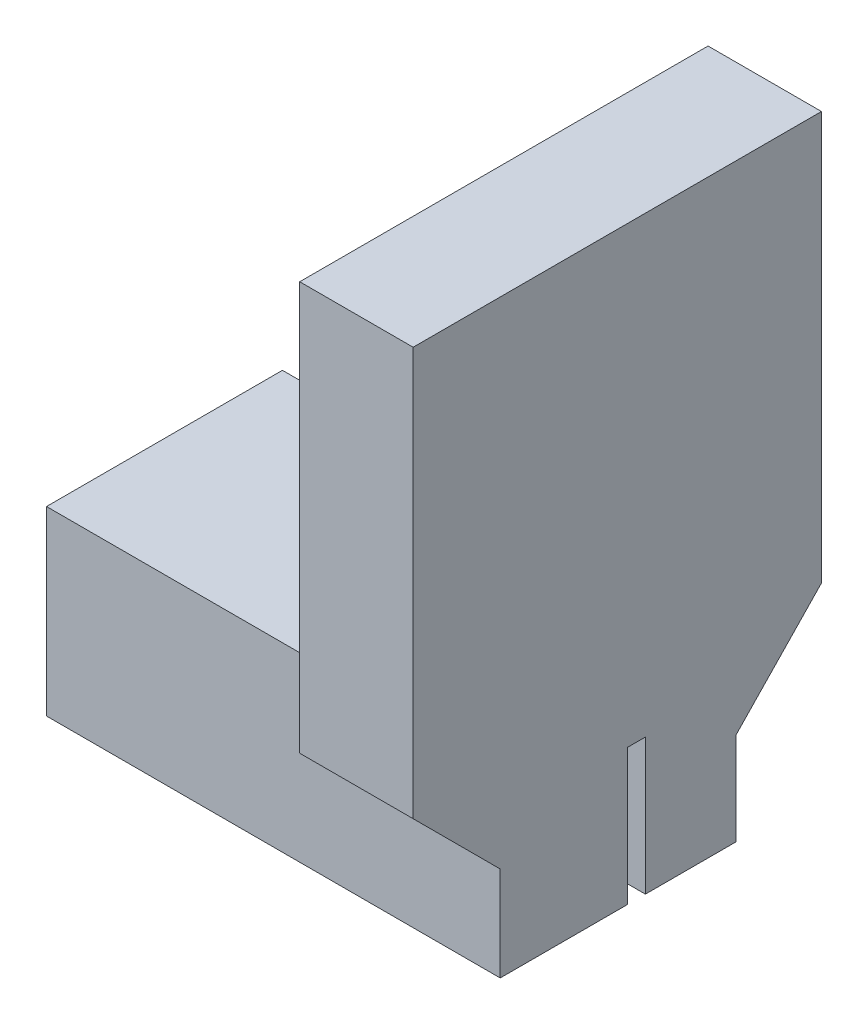
SolidWorks part; units mm, degrees
ref_plane "Front Plane" through (0, 0, 0) normal (0, 0, 1) x (1, 0, 0)
ref_plane "Top Plane" through (0, 0, 0) normal (0, 1, 0) x (1, 0, 0)
ref_plane "Right Plane" through (0, 0, 0) normal (1, 0, 0) x (0, 0, -1)
sketch "Sketch1" plane through (0, 0, 0) normal (0, 1, 0) x (1, 0, 0)
  line L0 (0, -1.2) -> (0, 1.2) construction
  line L2 (0, 1.2) -> (20, 1.2)
  line L3 (0, 1.2) -> (0, 5.2)
  line L4 (0, 5.2) -> (20, 5.2)
  line L5 (20, 1.2) -> (20, 5.2)
  line L6 (0, -1.2) -> (20, -1.2)
  line L7 (0, -1.2) -> (0, -5.2)
  line L8 (0, -5.2) -> (20, -5.2)
  line L9 (20, -1.2) -> (20, -5.2)
  point P5 (0, 0)
  dimension "D1" = 2.4
  dimension "D2" = 4
  dimension "D3" = 20
extrude "Boss-Extrude1" add sketch "Sketch1" along normal blind 6
sketch "Sketch3" plane through (0, 0, 0) normal (0, -1, 0) x (1, 0, 0)
  line L0 (17.4804, -0.4) -> (18, -0.4)
  line L1 (18, -0.4) -> (19.4804, -0.4) construction
  line L2 (19.4804, -0.4) -> (20, -0.4)
  line L3 (17.4804, -0.4) -> (17.4804, 1.2)
  line L4 (20, 1.2) -> (0, 1.2) construction
  line L5 (17.4804, 1.2) -> (20, 1.2)
  line L6 (0, -1.2) -> (20, -1.2) construction
  line L7 (20, -0.4) -> (20, 1.2)
  arc A0 (18, -0.4) -> (18.1487, -0.2696) centre (18, -0.25) ccw
  arc A1 (18.1487, -0.2696) -> (18.2413, 0.0382) centre (19.1402, -0.4) cw
  arc A2 (18.2413, 0.0382) -> (19.2391, 0.0382) centre (18.7402, -0.205) cw
  arc A3 (19.2391, 0.0382) -> (19.3316, -0.2696) centre (18.3402, -0.4) cw
  arc A4 (19.3316, -0.2696) -> (19.4804, -0.4) centre (19.4804, -0.25) ccw
  point P12 (17.7402, -0.4)
  dimension "D1" = 0.15
  dimension "D2" = 1
  dimension "D3" = 0.555
  dimension "D4" = 0.4
  dimension "D5" = 0.75
  dimension "D6" = 2
  dimension "D7" = 0.8
extrude "Boss-Extrude2" add sketch "Sketch3" against normal up to surface (6 mm away) up to face at (10, 6, 3.2)
pattern_linear "LPattern1" count 5 spacing 2 along (-1, 0, 0) of "Boss-Extrude2"
sketch "Sketch4" plane through (0, 6, 0) normal (0, 1, 0) x (1, 0, 0)
  line L1 (0, 5.2) -> (20, 5.2)
  line L2 (0, 5.2) -> (0, -5.2)
  line L3 (0, -5.2) -> (20, -5.2)
  line L4 (20, 5.2) -> (20, -5.2)
extrude "Boss-Extrude3" add sketch "Sketch4" along normal blind 2
sketch "Sketch5" plane through (20, 0, 0) normal (1, 0, 0) x (0, 0, -1)
  line L1 (-9.0382, 26) -> (8.9618, 26)
  line L2 (-9.0382, 26) -> (-9.0382, 8)
  line L4 (8.9618, 26) -> (8.9618, 8)
  line L5 (-0.0382, 0) -> (-0.0382, 26) construction
  line L6 (-9.0382, 8) -> (-5.2, 4.1618)
  line L7 (-5.2, 8) -> (-5.2, 0) construction
  line L8 (8.9618, 8) -> (5.2, 4.0869)
  line L9 (5.2, 8) -> (5.2, 0) construction
  line L10 (-5.2, 4.1618) -> (-5.2, 8)
  line L11 (-5.2, 8) -> (5.2, 8)
  line L12 (5.2, 8) -> (5.2, 4.0869)
  dimension "D1" = 18
  dimension "D2" = 18
  dimension "D3" = 45
extrude "Boss-Extrude4" add sketch "Sketch5" against normal blind 5
